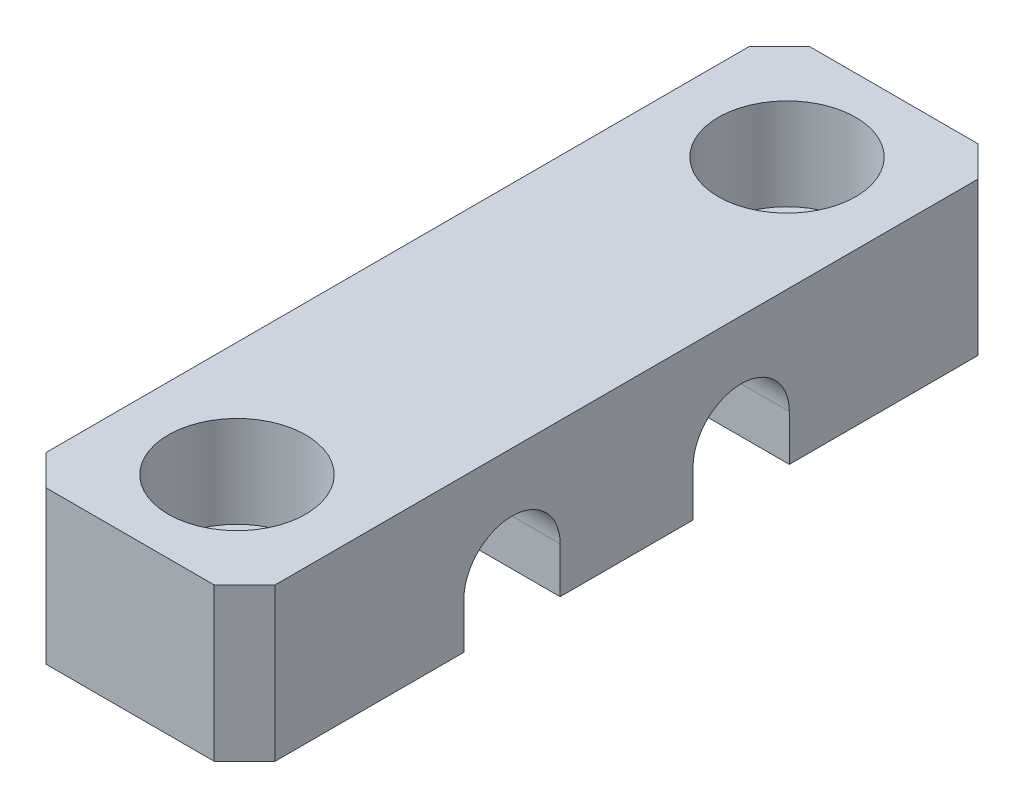
SolidWorks part; units mm, degrees
material "ABS"
ref_plane "Front Plane" through (0, 0, 0) normal (0, 0, 1) x (1, 0, 0)
ref_plane "Top Plane" through (0, 0, 0) normal (0, 1, 0) x (1, 0, 0)
ref_plane "Right Plane" through (0, 0, 0) normal (1, 0, 0) x (0, 0, -1)
sketch "Sketch1" plane through (0, 0, 0) normal (1, 0, 0) x (0, 0, -1)
  line L1 (-25, 5) -> (25, 5)
  line L2 (-25, 5) -> (-25, -5)
  line L3 (-25, -5) -> (25, -5)
  line L4 (25, 5) -> (25, -5)
  line L5 (-25, 5) -> (25, -5) construction
  line L6 (-25, -5) -> (25, 5) construction
  point P0 (0, 0)
  dimension "D1" = 50
  dimension "D2" = 10
extrude "Boss-Extrude1" add sketch "Sketch1" along normal blind 15
sketch "Sketch3" plane through (0, 5, 0) normal (0, 1, 0) x (1, 0, 0)
  line L0 (7.5, 18) -> (7.5, -18) construction
  line L1 (0, 25) -> (15, -25) construction
  circle A0 centre (7.5, -18) radius 4.5
  circle A1 centre (7.5, 18) radius 4.5
  point P6 (7.5, 0)
  dimension "D1" = 9
  dimension "D2" = 36
extrude "Cut-Extrude1" cut sketch "Sketch3" against normal blind 6
sketch "Sketch4" plane through (0, -1, 0) normal (0, 1, 0) x (1, 0, 0)
  circle A0 centre (7.5, 18) radius 3
  circle A1 centre (7.5, -18) radius 3
  dimension "D1" = 6
extrude "Cut-Extrude2" cut sketch "Sketch4" against normal blind 6
sketch "Sketch5" plane through (15, 0, 0) normal (1, 0, 0) x (0, 0, -1)
  line L0 (0, 0) -> (0, -2) construction
  line L1 (-7.5, -2) -> (7.5, -2) construction
  line L3 (-10.65, -2) -> (-4.35, -2)
  line L4 (-10.65, -2) -> (-10.65, -9.1854)
  line L5 (-10.65, -9.1854) -> (-4.35, -9.1854)
  line L6 (-4.35, -2) -> (-4.35, -9.1854)
  line L7 (4.35, -2) -> (10.65, -2)
  line L8 (4.35, -2) -> (4.35, -9.4809)
  line L9 (4.35, -9.4809) -> (10.65, -9.4809)
  line L10 (10.65, -2) -> (10.65, -9.4809)
  circle A0 centre (-7.5, -2) radius 3.15
  circle A1 centre (7.5, -2) radius 3.15
  line M4 (-25, -5) -> (25, -5)
  dimension "D2" = 6.3
  dimension "D1" = 15
  dimension "D3" = 2
extrude "Cut-Extrude3" cut sketch "Sketch5" against normal through all contours L3 A0 M4 | L3 A0 | A0 L4 L5 L6 M4 | A0 L4 M4 | A0 L6 M4 | A1 L8 M4 | L7 A1 M4 | L7 A1 | A1 L10 M4
chamfer "Chamfer1" distance 2 angle 45 4 edges at (0, 0, 25) (15, 0, 25) (0, 0, -25) (15, 0, -25)
